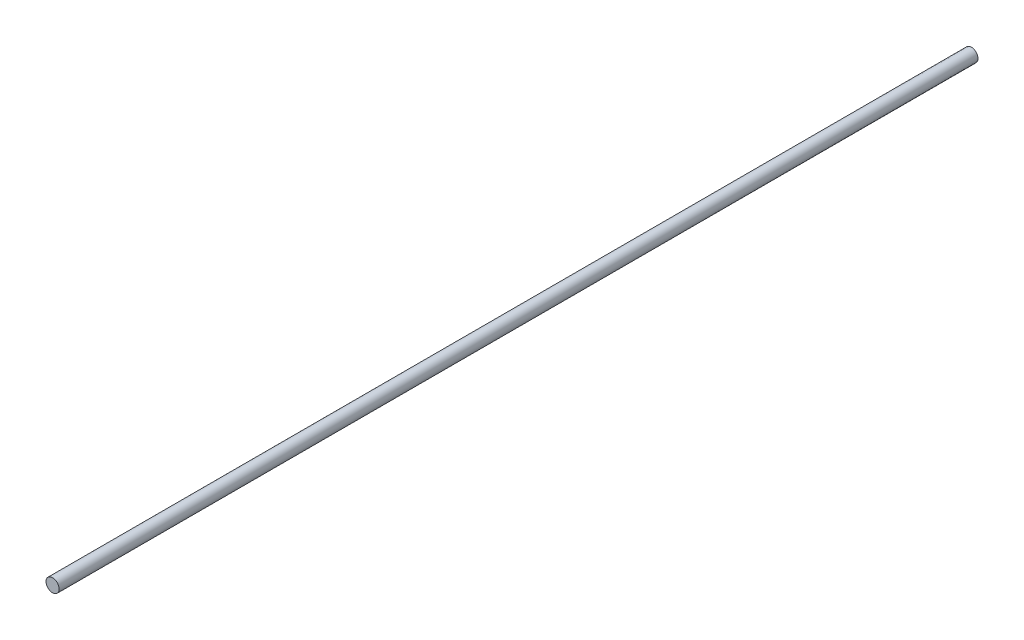
SolidWorks part; units mm, degrees
material "1.6657 (14NiCrMo13-4)"
ref_plane "Front Plane" through (0, 0, 0) normal (0, 0, 1) x (1, 0, 0)
ref_plane "Top Plane" through (0, 0, 0) normal (0, 1, 0) x (1, 0, 0)
ref_plane "Right Plane" through (0, 0, 0) normal (1, 0, 0) x (0, 0, -1)
sketch "Sketch2" plane through (0, 0, 0) normal (0, 0, 1) x (1, 0, 0)
  circle A0 centre (0, 0) radius 5
  dimension "D1" = 10
extrude "Boss-Extrude1" add sketch "Sketch2" along normal blind 700
